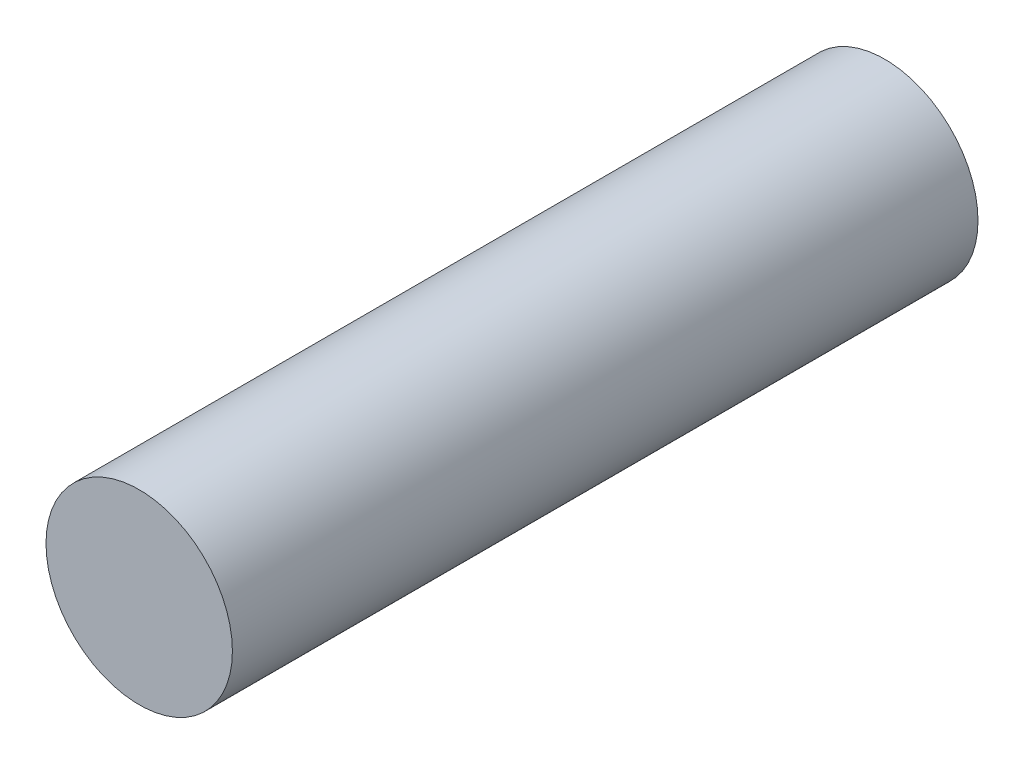
SolidWorks part; units mm, degrees
ref_plane "Front Plane" through (0, 0, 0) normal (0, 0, 1) x (1, 0, 0)
ref_plane "Top Plane" through (0, 0, 0) normal (0, 1, 0) x (1, 0, 0)
ref_plane "Right Plane" through (0, 0, 0) normal (1, 0, 0) x (0, 0, -1)
sketch "Sketch1" plane through (0, 0, 0) normal (0, 0, 1) x (1, 0, 0)
  circle A0 centre (0, 0) radius 75
  dimension "D1" = 150
extrude "Boss-Extrude1" add sketch "Sketch1" along normal blind 600
sketch "Sketch2" plane through (0, 0, 0) normal (0, 0, -1) x (-1, 0, 0)
  circle A0 centre (0, 0) radius 37.5
  dimension "D1" = 75
extrude "Cut-Extrude1" cut sketch "Sketch2" against normal blind 500
